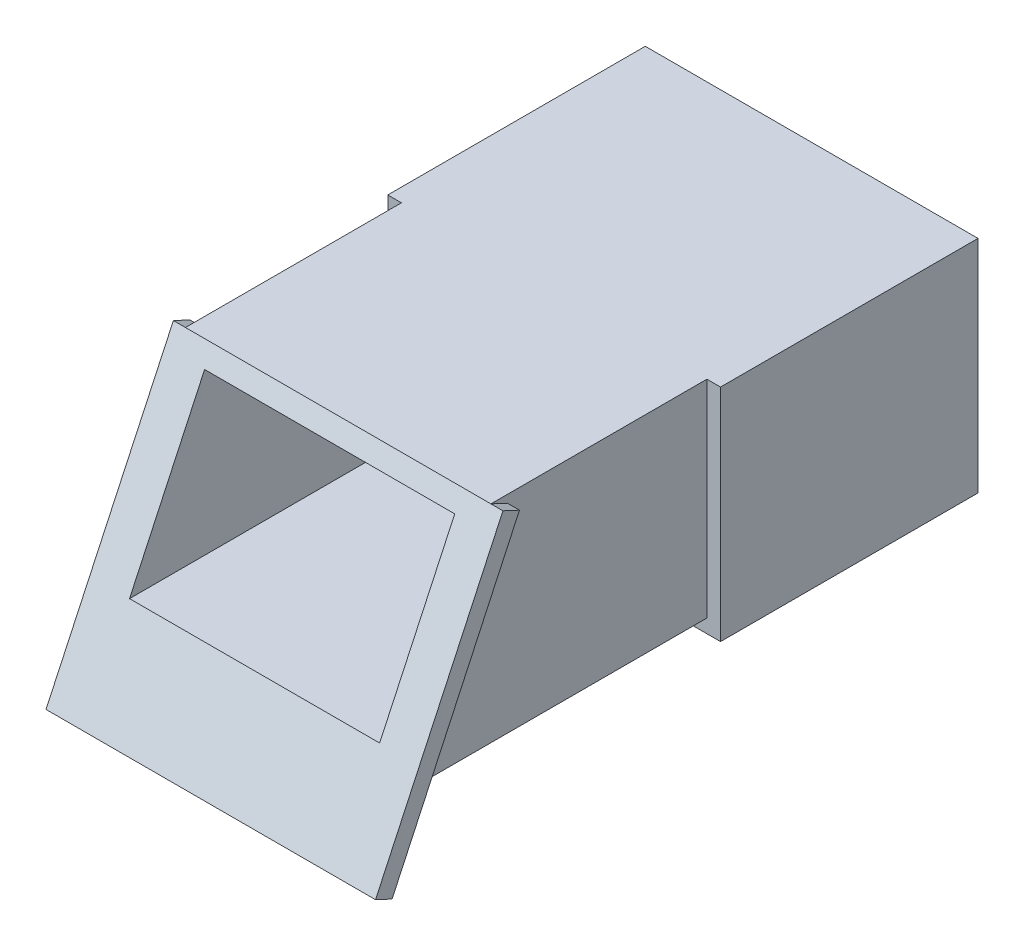
SolidWorks part; units mm, degrees
ref_plane "Alzado" through (0, 0, 0) normal (0, 0, 1) x (1, 0, 0)
ref_plane "Planta" through (0, 0, 0) normal (0, 1, 0) x (1, 0, 0)
ref_plane "Vista lateral" through (0, 0, 0) normal (1, 0, 0) x (0, 0, -1)
sketch "Croquis1" plane through (0, 0, 0) normal (0, 0, 1) x (1, 0, 0)
  line L1 (-37.1318, 17.9473) -> (16.1082, 17.9473)
  line L2 (-37.1318, 17.9473) -> (-37.1318, -17.3327)
  line L3 (-37.1318, -17.3327) -> (16.1082, -17.3327)
  line L4 (16.1082, 17.9473) -> (16.1082, -17.3327)
  line L5 (-33.9518, 15.0273) -> (12.9282, 15.0273)
  line L6 (-33.9518, 15.0273) -> (-33.9518, -14.1527)
  line L7 (-33.9518, -14.1527) -> (12.9282, -14.1527)
  line L8 (12.9282, 15.0273) -> (12.9282, -14.1527)
  dimension "D1" = 53.24
  dimension "D2" = 35.28
  dimension "D3" = 3.18
  dimension "D4" = 3.18
  dimension "D5" = 3.18
  dimension "D6" = 2.92
extrude "Saliente-Extruir2" add sketch "Croquis1" along normal blind 41.2
sketch "Croquis3" plane through (0, 0, 41.2) normal (0, 0, 1) x (1, 0, 0)
  line L1 (-34.9518, -15.1527) -> (13.9282, -15.1527)
  line L2 (-34.9518, -15.1527) -> (-34.9518, 17.9473)
  line L3 (-34.9518, 17.9473) -> (13.9282, 17.9473)
  line L4 (13.9282, -15.1527) -> (13.9282, 17.9473)
  line L5 (12.9282, -14.1527) -> (12.9282, 15.0273) construction
  line L6 (-30.5218, 15.0273) -> (9.4982, 15.0273)
  line L7 (9.4982, 15.0273) -> (-30.5218, 15.0273)
  line L8 (9.4982, 15.0273) -> (9.4982, -10.7227)
  line L9 (9.4982, -10.7227) -> (-30.5218, -10.7227)
  line L10 (-30.5218, 15.0273) -> (-30.5218, -10.7227)
  line L11 (-30.5218, 15.0273) -> (-30.5218, -10.7227)
  line L12 (-34.9518, 17.9473) -> (13.9282, 17.9473)
  line L13 (-34.9518, 17.9473) -> (-34.9518, -15.1527)
  line L14 (-34.9518, -15.1527) -> (13.9282, -15.1527)
  line L15 (13.9282, 17.9473) -> (13.9282, -15.1527)
  line L16 (-30.5218, 15.0273) -> (9.4982, 15.0273)
  line L17 (-30.5218, 15.0273) -> (-30.5218, -10.7227)
  line L18 (-30.5218, -10.7227) -> (9.4982, -10.7227)
  line L19 (9.4982, 15.0273) -> (9.4982, -10.7227)
  line L20 (13.9282, -15.1527) -> (-34.9518, -15.1527)
  line L21 (13.9282, -15.1527) -> (13.9282, 17.9473)
  line L22 (13.9282, 17.9473) -> (-34.9518, 17.9473)
  line L23 (-34.9518, -15.1527) -> (-34.9518, 17.9473)
  line L24 (9.4982, -10.7227) -> (-30.5218, -10.7227)
  line L25 (9.4982, -10.7227) -> (9.4982, 15.0273)
  line L26 (9.4982, 15.0273) -> (-30.5218, 15.0273)
  line L27 (-30.5218, -10.7227) -> (-30.5218, 15.0273)
  line L28 (-30.5218, -10.7227) -> (9.4982, -10.7227)
  line L29 (9.4982, 15.0273) -> (9.4982, -10.7227)
  dimension "D1" = 1
  dimension "D2" = 25.75
  dimension "D3" = 4.43
  dimension "D4" = 40.02
  dimension "D5" = 4.43
extrude "Saliente-Extruir11" add sketch "Croquis3" along normal blind 50 contours L10 L9 L8 L7 | L2 L3 L4 L1
sketch "Croquis15" plane through (0, 0, 91.2) normal (0, 0, 1) x (1, 0, 0)
  line L1 (15.8532, -30.2747) -> (-36.8768, -30.2747)
  line L2 (15.8532, -30.2747) -> (15.8532, 17.9453)
  line L3 (15.8532, 17.9453) -> (-36.8768, 17.9453)
  line L4 (-36.8768, -30.2747) -> (-36.8768, 17.9453)
  line L5 (13.9282, -15.1527) -> (13.9282, 17.9473) construction
  line L6 (-34.9518, -15.1527) -> (-34.9518, 17.9473) construction
  line L7 (-34.9518, -15.1527) -> (13.9282, -15.1527) construction
  line L10 (-30.5218, 15.0273) -> (9.4982, 15.0273)
  line L11 (-30.5218, 15.0273) -> (-30.5218, -10.7227)
  line L12 (-30.5218, -10.7227) -> (9.4982, -10.7227)
  line L13 (9.4982, 15.0273) -> (9.4982, -10.7227)
  dimension "D1" = 48.22
  dimension "D2" = 1.925
  dimension "D3" = 52.73
  dimension "D4" = 1.925
  dimension "D5" = 15.122
extrude "Saliente-Extruir13" [suppressed] add sketch "Croquis15" along normal blind 2.92
sketch "Croquis16" plane through (-34.9518, 0, 0) normal (-1, 0, 0) x (0, 0, 1)
  line L0 (91.2, -15.1527) -> (75.7593, 17.9473)
  line L1 (91.2, 17.9473) -> (41.2, 17.9473) construction
sketch "Croquis17" plane through (0, 17.9473, 0) normal (0, 1, 0) x (1, 0, 0)
  line L0 (-34.9518, -75.7593) -> (13.9282, -75.7593)
  line L1 (13.9282, -91.2) -> (13.9282, -41.2) construction
sketch "Croquis19" plane through (0, 0, 91.2) normal (0, 0, 1) x (1, 0, 0)
  line L0 (13.9282, -15.1527) -> (-34.9518, -15.1527)
sketch "Croquis20" plane through (13.9282, 0, 0) normal (1, 0, 0) x (0, 0, -1)
  line L0 (-75.7593, 17.9473) -> (-91.2, -15.1527)
ref_plane "Plano6" through (0, 32.2321, 69.0956) normal (0, -0.4228, -0.9062) x (-1, 0, 0)
sketch "Croquis21" plane through (0, 32.2321, 69.0956) normal (0, -0.4228, -0.9062) x (-1, 0, 0)
  line L1 (36.4325, -14.845) -> (-14.788, -14.845)
  line L2 (36.4325, -14.845) -> (36.4325, -53.2486)
  line L3 (36.4325, -53.2486) -> (-14.788, -53.2486)
  line L4 (-14.788, -14.845) -> (-14.788, -53.2486)
extrude "Cortar-Extruir1" cut sketch "Croquis21" against normal blind 24
sketch "Croquis22" plane through (0, 32.2321, 69.0956) normal (0, -0.4228, -0.9062) x (-1, 0, 0)
  line L0 (34.9518, -15.7626) -> (-13.9282, -15.7626) construction
  line L1 (36.8768, -15.7626) -> (-15.8532, -15.7626)
  line L2 (36.8768, -15.7626) -> (36.8768, -63.9826)
  line L3 (36.8768, -63.9826) -> (-15.8532, -63.9826)
  line L4 (-15.8532, -15.7626) -> (-15.8532, -63.9826)
  line L5 (34.9518, -52.2869) -> (34.9518, -15.7626) construction
  line L6 (-13.9282, -15.7626) -> (-13.9282, -52.2869) construction
  dimension "D1" = 52.73
  dimension "D2" = 48.22
  dimension "D3" = 0
  dimension "D4" = 1.925
  dimension "D5" = 1.925
extrude "Saliente-Extruir15" add sketch "Croquis22" along normal blind 2.92
ref_plane "Plano7" through (0, 0, 41.2) normal (0, 0, 1) x (1, 0, 0)
sketch "Croquis24" plane through (0, 0, 41.2) normal (0, 0, 1) x (1, 0, 0)
  line L1 (9.4982, 15.0273) -> (-30.5218, 15.0273)
  line L2 (9.4982, 15.0273) -> (9.4982, -10.7227)
  line L3 (9.4982, -10.7227) -> (-30.5218, -10.7227)
  line L4 (-30.5218, 15.0273) -> (-30.5218, -10.7227)
extrude "Cortar-Extruir2" cut sketch "Croquis24" along normal blind 81.92
